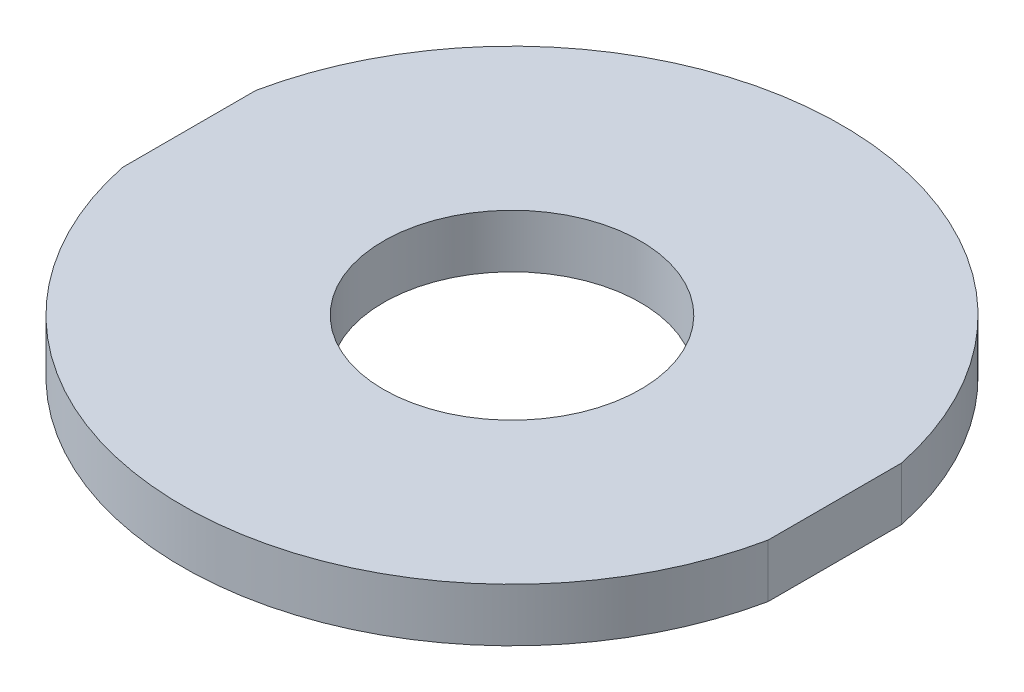
SolidWorks part; units mm, degrees
material "ABS"
ref_plane "Front Plane" through (0, 0, 0) normal (0, 0, 1) x (1, 0, 0)
ref_plane "Top Plane" through (0, 0, 0) normal (0, 1, 0) x (1, 0, 0)
ref_plane "Right Plane" through (0, 0, 0) normal (1, 0, 0) x (0, 0, -1)
sketch "Sketch1" plane through (0, 0, 0) normal (0, 1, 0) x (0.9995, 0, 0.031)
  line L2 (-90.2905, 8.0032) -> (-89.5143, -16.9848)
  line L3 (30.7312, 11.7621) -> (31.5073, -13.2259)
  arc A0 (30.7312, 11.7621) -> (-90.2905, 8.0032) centre (-29.3916, -2.6114) ccw
  arc A1 (-89.5143, -16.9848) -> (31.5073, -13.2259) centre (-29.3916, -2.6114) ccw
  circle A3 centre (-29.3916, -2.6114) radius 24.116
extrude "Boss-Extrude1" add sketch "Sketch1" along normal blind 10
